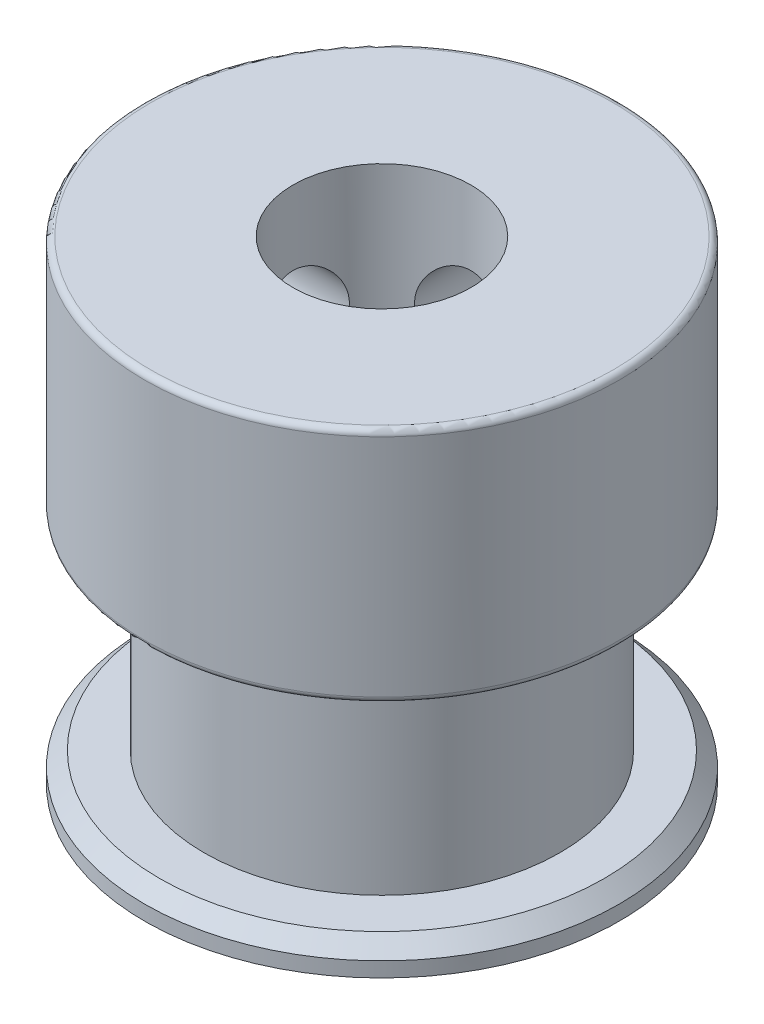
SolidWorks part; units mm, degrees
ref_plane "前视基准面" through (0, 0, 0) normal (0, 0, 1) x (1, 0, 0)
ref_plane "上视基准面" through (0, 0, 0) normal (0, 1, 0) x (1, 0, 0)
ref_plane "右视基准面" through (0, 0, 0) normal (1, 0, 0) x (0, 0, -1)
sketch "Sketch1" plane through (0, 0, 0) normal (0, 0, 1) x (1, 0, 0)
  line L1 (0, 0) -> (8, 0)
  line L2 (8, 0) -> (8, 1)
  line L3 (8, 1) -> (6, 1)
  line L4 (6, 1) -> (6, 8)
  line L5 (6, 8) -> (8, 8)
  line L6 (8, 8) -> (8, 16)
  line L7 (8, 16) -> (0, 16)
  line L8 (0, 16) -> (0, 0)
  dimension "D1" = 7
  dimension "D2" = 16
  dimension "D3" = 1
  dimension "D4" = 8
  dimension "D5" = 6
revolve "Revolve1" add sketch "Sketch1" angle 360 about L8
chamfer "Chamfer1" distance 0.5 angle 45 1 edges at (-8, 1, 0)
sketch "Sketch2" plane through (0, 16, 0) normal (0, 1, 0) x (1, 0, 0)
  circle A0 centre (0, 0) radius 3
  dimension "D1" = 6
extrude "Cut-Extrude1" cut sketch "Sketch2" against normal through all
sketch "Sketch3" plane through (0, 0, 0) normal (1, 0, 0) x (0, 0, -1)
  line L0 (-8, 12) -> (8, 12) construction
  line L1 (-8, 16) -> (-8, 8) construction
  line L2 (8, 8) -> (8, 16) construction
  circle A0 centre (0, 12) radius 1.5
  point P2 (0, 12)
  dimension "D1" = 3
extrude "Cut-Extrude2" cut sketch "Sketch3" against normal through all
sketch "Sketch4" plane through (0, 0, 0) normal (0, 0, 1) x (1, 0, 0)
  line L0 (8, 12) -> (-7.8581, 12) construction
  line L1 (8, 8) -> (8, 16) construction
  circle A0 centre (0, 12) radius 1.5
  spline S0 degree 2 poles (-8, 13.5) (-7.7188, 12) (-8, 10.5) knots 0 0 0 1 1 1 weights 0.0065 0.008 0.0095 construction
  dimension "D1" = 3
extrude "Cut-Extrude3" cut sketch "Sketch4" against normal through all
fillet "Fillet1" radius 0.2 2 edges at (-8, 16, 0) (-8, 8, 0)
